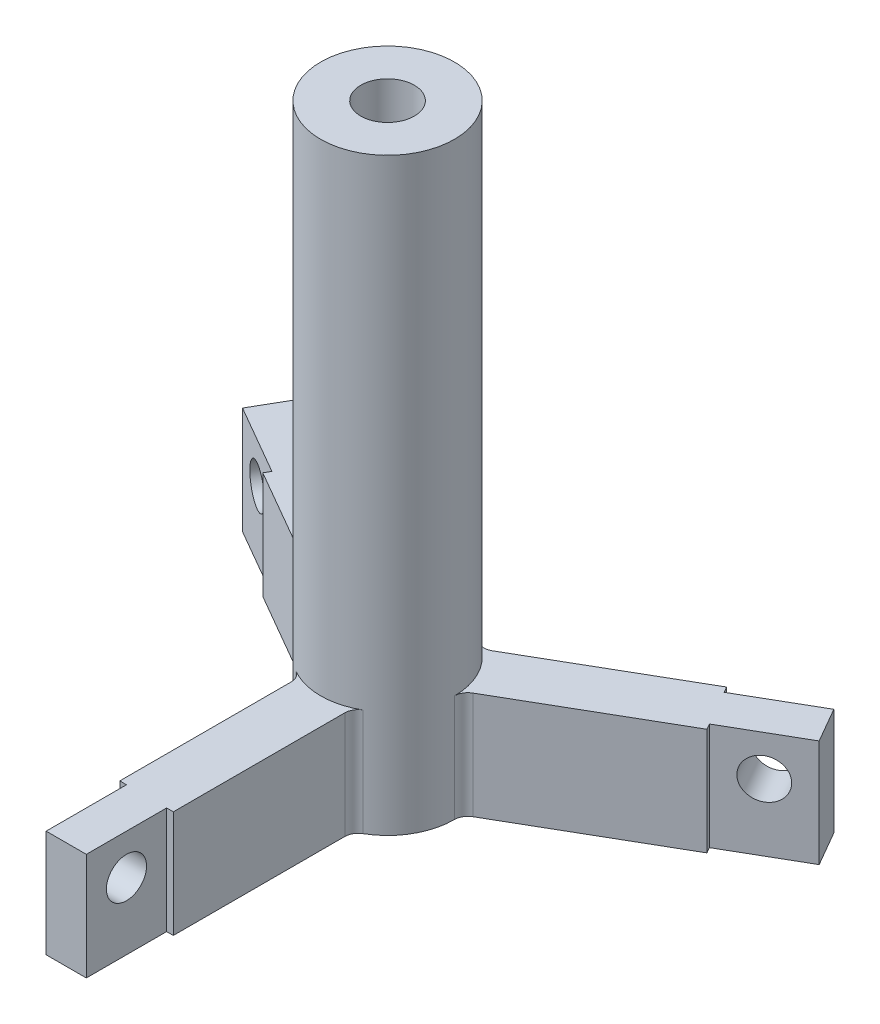
SolidWorks part; units mm, degrees
ref_plane "Front" through (0, 0, 0) normal (0, 0, 1) x (1, 0, 0)
ref_plane "Top" through (0, 0, 0) normal (0, 1, 0) x (1, 0, 0)
ref_plane "Right" through (0, 0, 0) normal (1, 0, 0) x (0, 0, -1)
other "Configuration Table"
sketch "Sketch1" plane through (0, 0, 0) normal (0, 0, 1) x (1, 0, 0)
  line L0 (0, 118.2237) -> (0, -58.1736) construction
  line L1 (12.7, 0) -> (12.7, 127)
  line L2 (12.7, 127) -> (6.35, 127)
  line L3 (6.35, 127) -> (6.35, 139.7)
  line L4 (6.35, 139.7) -> (15.875, 139.7)
  line L5 (15.875, 139.7) -> (15.875, 0)
  line L6 (15.875, 0) -> (12.7, 0)
  dimension "D1" = 25.4
  dimension "D2" = 31.75
  dimension "D3" = 12.7
  dimension "D4" = 139.7
  dimension "D5" = 127
revolve "Base-Revolve" add sketch "Sketch1" angle 360 about L0
ref_plane "Plane1" through (0, 0, 76.2) normal (0, 0, 1) x (1, 0, 0)
sketch "Sketch2" plane through (0, 0, 76.2) normal (0, 0, 1) x (1, 0, 0)
  line L1 (-4.7625, 0) -> (4.7625, 0)
  line L2 (-4.7625, 0) -> (-4.7625, 25.4)
  line L3 (-4.7625, 25.4) -> (4.7625, 25.4)
  line L4 (4.7625, 0) -> (4.7625, 25.4)
  point P4 (0, 0)
  dimension "D1" = 25.4
  dimension "D2" = 9.525
extrude "Boss-Extrude1" add sketch "Sketch2" against normal up to surface (61.0562 mm away)
sketch "Sketch3" plane through (4.7625, 0, 0) normal (1, 0, 0) x (0, 0, -1)
  line L0 (-76.2, 0) -> (-76.2, 25.4) construction
  line L1 (-15.1438, 25.4) -> (-76.2, 25.4) construction
  circle A0 centre (-66.675, 15.875) radius 4.7625
  dimension "D1" = 9.525
  dimension "D2" = 9.525
  dimension "D3" = 9.525
extrude "Cut-Extrude1" cut sketch "Sketch3" against normal through all
ref_plane "Plane2" through (0, 0, 57.15) normal (0, 0, 1) x (1, 0, 0)
sketch "Sketch4" plane through (0, 0, 57.15) normal (0, 0, 1) x (1, 0, 0)
  line L0 (4.7625, 25.4) -> (-4.7625, 25.4) construction
  line L1 (6.35, 0) -> (-6.35, 0)
  line L2 (6.35, 0) -> (6.35, 25.4)
  line L3 (6.35, 25.4) -> (-6.35, 25.4)
  line L4 (-6.35, 0) -> (-6.35, 25.4)
  point P4 (0, 0)
  dimension "D1" = 12.7
extrude "Boss-Extrude2" add sketch "Sketch4" against normal up to surface (42.6003 mm away)
fillet "Fillet1" radius 3.175 2 edges at (-6.35, 12.7, 14.5497) (6.35, 12.7, 14.5497)
pattern_circular "CirPattern1" count 3 over 360 about axis through (0, 0, 0) along (0, 1, 0) of "Fillet1", "Boss-Extrude2", "Cut-Extrude1", "Boss-Extrude1"
ref_plane "Plane3" through (0, 0, -15.875) normal (0, 0, 1) x (1, 0, 0)
sketch "Sketch5" plane through (0, 0, -15.875) normal (0, 0, 1) x (1, 0, 0)
  line L0 (0, 118.2237) -> (0, -58.1736) construction
  circle A0 centre (0, 38.1) radius 7.9375
  dimension "D1" = 15.875
  dimension "D2" = 38.1
extrude "Cut-Extrude3" cut sketch "Sketch5" along normal blind 0.635
sketch "Sketch6" plane through (0, 0, -15.24) normal (0, 0, -1) x (-1, 0, 0)
  circle A0 centre (0, 38.1) radius 3.175
  arc A1 (4.445, 44.6762) -> (-4.445, 44.6762) centre (0, 38.1) ccw construction
  dimension "D1" = 6.35
extrude "Cut-Extrude4" cut sketch "Sketch6" against normal blind 12.7
